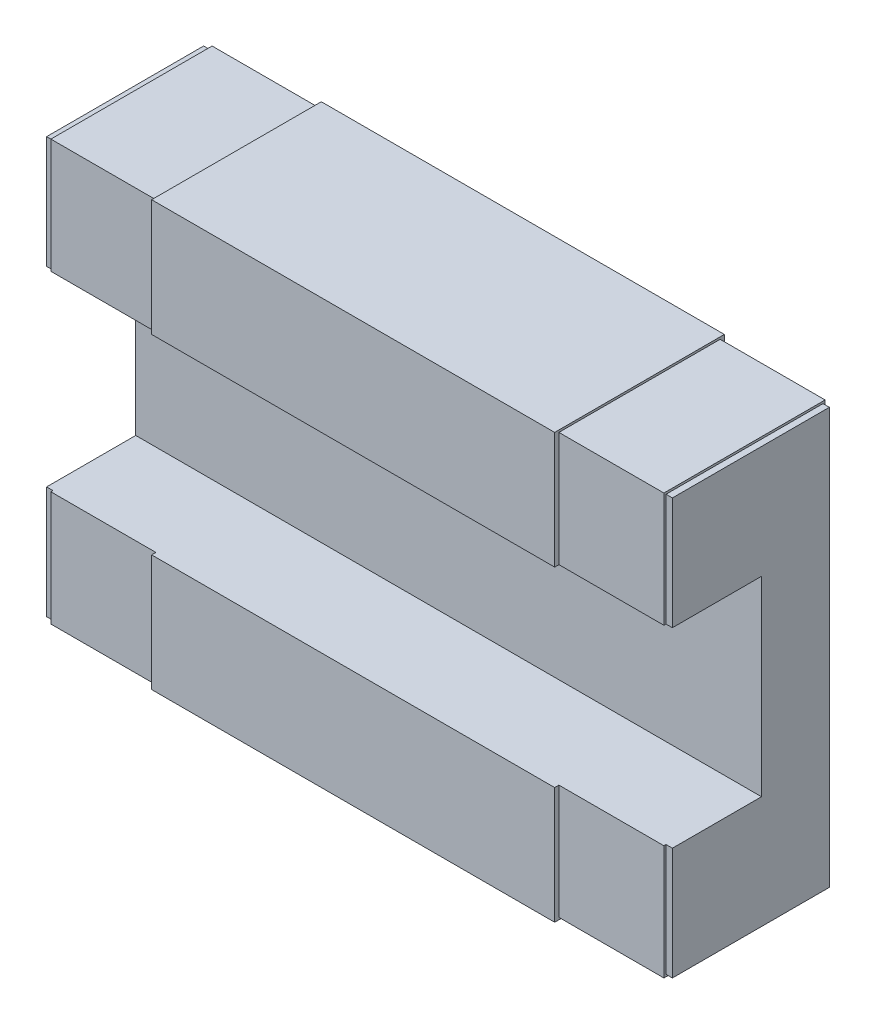
SolidWorks part; units mm, degrees
ref_plane "Plan de face" through (0, 0, 0) normal (0, 0, 1) x (1, 0, 0)
ref_plane "Plan de dessus" through (0, 0, 0) normal (0, 1, 0) x (1, 0, 0)
ref_plane "Plan de droite" through (0, 0, 0) normal (1, 0, 0) x (0, 0, -1)
sketch "Esquisse1" plane through (0, 0, 0) normal (0, 0, 1) x (1, 0, 0)
  line L1 (14.75, -10) -> (-14.75, -10)
  line L2 (14.75, -10) -> (14.75, 10)
  line L3 (14.75, 10) -> (-14.75, 10)
  line L4 (-14.75, -10) -> (-14.75, 10)
  line L5 (14.75, -10) -> (-14.75, 10) construction
  line L6 (14.75, 10) -> (-14.75, -10) construction
  point P0 (0, 0)
  dimension "D1" = 20
  dimension "D2" = 29.5
extrude "Boss.-Extru.1" add sketch "Esquisse1" along normal mid plane 8
sketch "Esquisse2" plane through (14.75, 0, 0) normal (1, 0, 0) x (0, 0, -1)
  line L0 (-4, 4.5) -> (0.5, 4.5)
  line L1 (-4, -10) -> (-4, 10) construction
  line L2 (0.5, 4.5) -> (0.5, -4.5)
  line L3 (0.5, -4.5) -> (-4, -4.5)
  line L4 (-4, 4.5) -> (-4, -4.5)
  point P4 (0.5, 0)
  dimension "D1" = 4.5
  dimension "D2" = 9
extrude "Enlèv. mat.-Extru.1" cut sketch "Esquisse2" against normal through all and the other way through all
sketch "Esquisse3" plane through (0, 0, -4) normal (0, 0, -1) x (-1, 0, 0)
  line L6 (-9.5, -5) -> (9.5, -5)
  line L12 (9.5, 5) -> (-9.5, 5)
  line L14 (-9.5, 5) -> (-9.5, -5)
  line L15 (9.5, 5) -> (9.5, -5)
  point P0 (9.5, 0)
  point P21 (0, -5)
  dimension "D1" = 19
  dimension "D3" = 10
extrude "Enlèv. mat.-Extru.2" cut sketch "Esquisse3" against normal blind 0.1
sketch "Esquisse4" plane through (0, 0, -4) normal (0, 0, -1) x (-1, 0, 0)
  line L0 (14.75, -10) -> (-14.75, -10) construction
  line L1 (-14.75, 10) -> (-9.5, 10)
  line L2 (-14.75, 10) -> (-14.75, -10)
  line L3 (-14.75, -10) -> (-9.5, -10)
  line L4 (-9.5, 10) -> (-9.5, -10)
  line L5 (-14.75, 10) -> (14.75, 10) construction
  line L6 (14.75, -10) -> (9.5, -10)
  line L7 (14.75, -10) -> (14.75, 10)
  line L8 (14.75, 10) -> (9.5, 10)
  line L9 (9.5, -10) -> (9.5, 10)
  line L10 (9.5, -5) -> (9.5, 5) construction
  line L11 (-9.5, 5) -> (-9.5, -5) construction
extrude "Enlèv. mat.-Extru.3" cut sketch "Esquisse4" against normal blind 0.2
sketch "Esquisse5" plane through (0, 0, -3.8) normal (0, 0, -1) x (-1, 0, 0)
  line L0 (-14.75, -10) -> (-9.5, -10) construction
  line L1 (-14.75, 10) -> (-14.45, 10)
  line L2 (-14.75, 10) -> (-14.75, -10)
  line L3 (-14.75, -10) -> (-14.45, -10)
  line L4 (-14.45, 10) -> (-14.45, -10)
  line L5 (9.5, -10) -> (14.75, -10) construction
  line L6 (14.75, 10) -> (14.45, 10)
  line L7 (14.75, 10) -> (14.75, -10)
  line L8 (14.75, -10) -> (14.45, -10)
  line L9 (14.45, 10) -> (14.45, -10)
  dimension "D1" = 0.3
extrude "Enlèv. mat.-Extru.4" cut sketch "Esquisse5" against normal blind 0.1
sketch "Esquisse6" plane through (0, -10, 0) normal (0, -1, 0) x (1, 0, 0)
  line L1 (9.5, -3.8) -> (14.75, -3.8)
  line L2 (9.5, -3.8) -> (9.5, 4)
  line L3 (9.5, 4) -> (14.75, 4)
  line L4 (14.75, -3.8) -> (14.75, 4)
  line L5 (-9.5, -3.8) -> (-14.75, -3.8)
  line L6 (-9.5, -3.8) -> (-9.5, 4)
  line L7 (-9.5, 4) -> (-14.75, 4)
  line L8 (-14.75, -3.8) -> (-14.75, 4)
extrude "Enlèv. mat.-Extru.5" cut sketch "Esquisse6" against normal blind 0.1
sketch "Esquisse7" plane through (0, -9.9, 0) normal (0, -1, 0) x (1, 0, 0)
  line L1 (-14.45, -3.8) -> (-14.75, -3.8)
  line L2 (-14.45, -3.8) -> (-14.45, 4)
  line L3 (-14.45, 4) -> (-14.75, 4)
  line L4 (-14.75, -3.8) -> (-14.75, 4)
  line L5 (14.45, -3.8) -> (14.75, -3.8)
  line L6 (14.45, -3.8) -> (14.45, 4)
  line L7 (14.45, 4) -> (14.75, 4)
  line L8 (14.75, -3.8) -> (14.75, 4)
extrude "Enlèv. mat.-Extru.6" cut sketch "Esquisse7" against normal blind 0.1
mirror "Symétrie2" about plane through (0, 0, 0) normal (0, 0, 1) of "Enlèv. mat.-Extru.4", "Enlèv. mat.-Extru.3" second plane through (0, 0, 0) second plane normal (0, 1, 0)
mirror "Symétrie3" about plane through (0, 0, 0) normal (0, 1, 0) of "Enlèv. mat.-Extru.6", "Enlèv. mat.-Extru.5"
hole_wizard "Trou pour taraudage pour trou taraudé M31" positions "Esquisse8" profile "Esquisse9" hole size "M3" standard "ISO"
sketch "Esquisse8" plane through (0, 0, -4) normal (0, 0, -1) x (-1, 0, 0)
  line L1 (-5, 7.5) -> (5, 7.5)
  line L2 (-5, 7.5) -> (-5, -7.5)
  line L3 (-5, -7.5) -> (5, -7.5)
  line L4 (5, 7.5) -> (5, -7.5)
  line L5 (-5, 7.5) -> (5, -7.5) construction
  line L7 (-5, -7.5) -> (5, 7.5) construction
  line L9 (0, 7.5) -> (0, 5) construction
  line L10 (9.5, 5) -> (-9.5, 5) construction
  line L12 (0, 7.5) -> (0, 10) construction
  line L13 (-9.5, 10) -> (9.5, 10) construction
  point P0 (-5, 7.5)
  point P2 (5, 7.5)
  point P4 (-5, -7.5)
  point P6 (5, -7.5)
  dimension "D1" = 10
sketch "Esquisse9" plane through (5, 7.5, -4) normal (1, 0, 0) x (0, 1, 0)
  line L0 (0, 0) -> (0, 4.7511)
  line L1 (0, 4.7511) -> (1.25, 4)
  line L2 (1.25, 4) -> (1.25, 0)
  line L5 (1.25, 0) -> (0, 0)
  line L10 (0, 4.7511) -> (-1.25, 4) construction
  line L11 (0, -6.35) -> (0, 107.95) construction
  dimension "Diamètre du perçage" = 2.5
  dimension "Profondeur du perçage" = 4
  dimension "Angle de pointe" = 118
